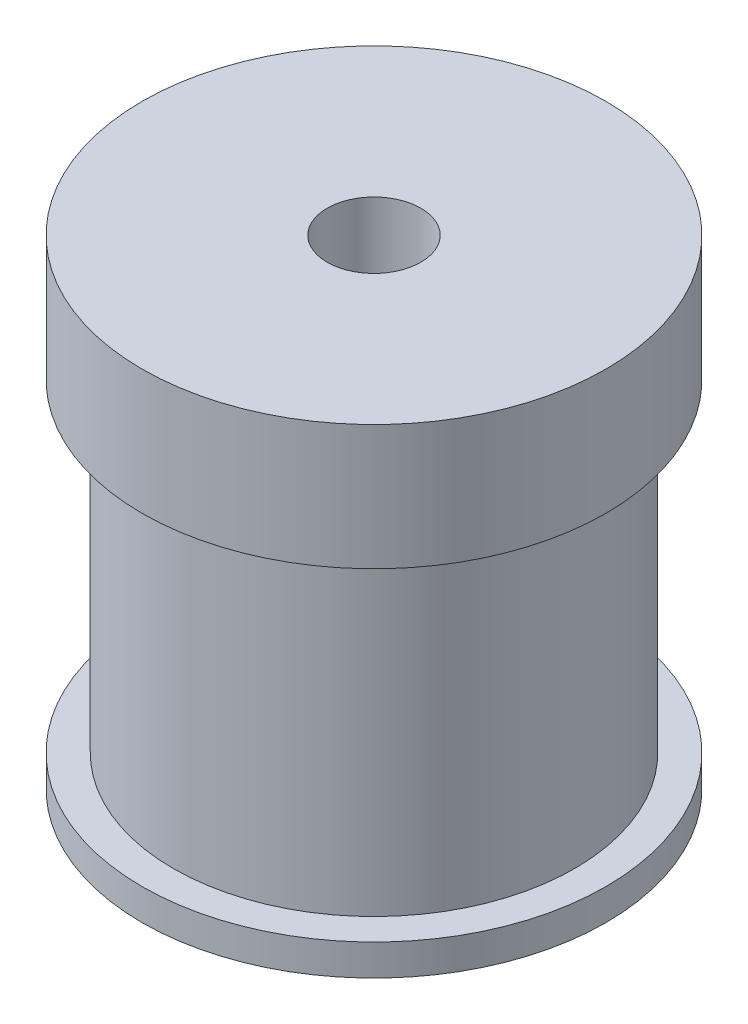
SolidWorks part; units mm, degrees
ref_plane "Front Plane" through (0, 0, 0) normal (0, 0, 1) x (1, 0, 0)
ref_plane "Top Plane" through (0, 0, 0) normal (0, 1, 0) x (1, 0, 0)
ref_plane "Right Plane" through (0, 0, 0) normal (1, 0, 0) x (0, 0, -1)
sketch "Sketch1" plane through (0, 0, 0) normal (0, 1, 0) x (1, 0, 0)
  circle A0 centre (0, 0) radius 7.425
  dimension "D1" = 14.85
extrude "Boss-Extrude1" add sketch "Sketch1" along normal blind 1
sketch "Sketch2" plane through (0, 1, 0) normal (0, 1, 0) x (1, 0, 0)
  circle A0 centre (0, 0) radius 6.425
  dimension "D1" = 12.85
extrude "Boss-Extrude2" add sketch "Sketch2" along normal blind 10.35
sketch "Sketch3" plane through (0, 11.35, 0) normal (0, 1, 0) x (1, 0, 0)
  circle A0 centre (0, 0) radius 7.425
  dimension "D1" = 14.85
extrude "Boss-Extrude3" add sketch "Sketch3" along normal blind 4
sketch "Sketch4" plane through (0, 15.35, 0) normal (0, 1, 0) x (1, 0, 0)
  circle A0 centre (0, 0) radius 1.5
  dimension "D1" = 3
extrude "Cut-Extrude1" cut sketch "Sketch4" against normal blind 15.35
